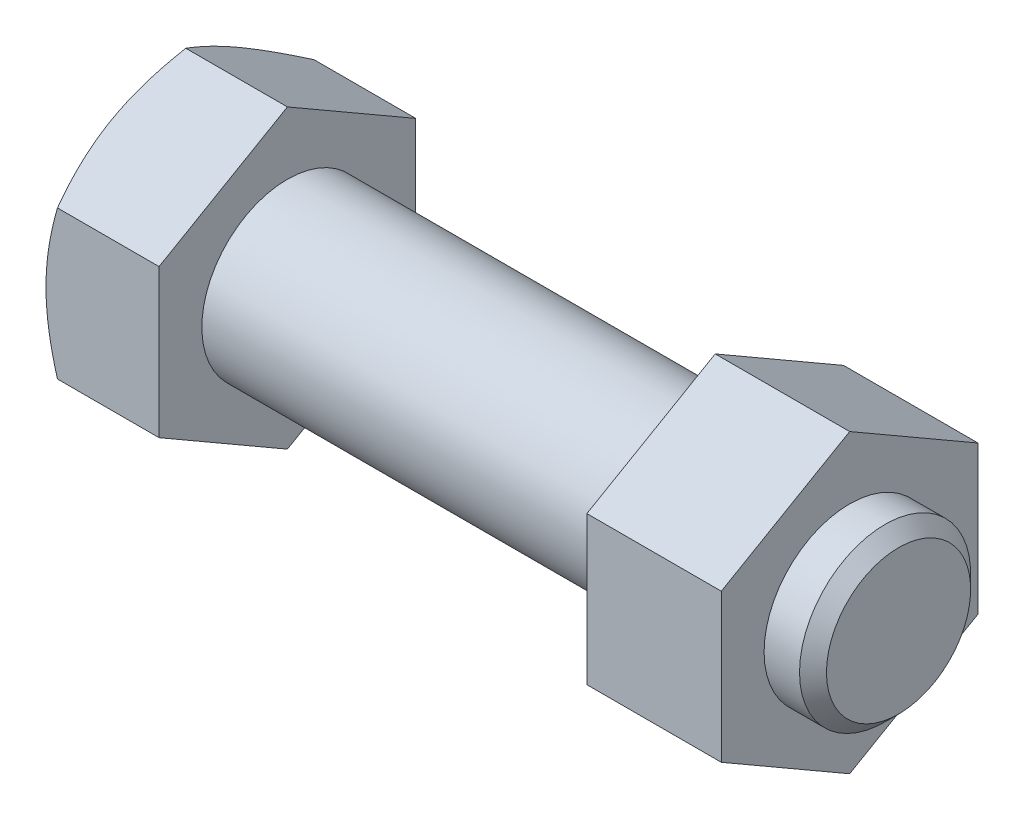
SolidWorks part; units mm, degrees
extrude "BaseHead" add sketch "Sketch1" along normal blind 9.25
sketch "Sketch1" plane through (0, 0, 0) normal (1, 0, 0) x (0, 0, -1)
  line L0 (10.5, 6.0622) -> (10.5, -6.0622)
  line L1 (-10.5, 6.0622) -> (-10.5, -6.0622)
  line L2 (10.5, -6.0622) -> (0, -12.1244)
  line L3 (0, -12.1244) -> (-10.5, -6.0622)
  line L4 (10.5, 6.0622) -> (0, 12.1244)
  line L5 (0, 12.1244) -> (-10.5, 6.0622)
  dimension "Width_flats" = 21
  dimension "D2" = 120
  dimension "D3" = 10.5
  dimension "D4" = 10.5
  dimension "D5" = 10.5
material "Dacromet"
ref_plane "Plane1" through (0, 0, 0) normal (0, 0, 1) x (1, 0, 0)
ref_plane "Plane2" through (0, 0, 0) normal (0, 1, 0) x (1, 0, 0)
ref_plane "Plane3" through (0, 0, 0) normal (1, 0, 0) x (0, 0, -1)
sketch "BodySke" plane through (0, 0, 0) normal (0, 0, 1) x (1, 0, 0)
  line L0 (0, 6.0622) -> (0, -6.0622) construction
  line L1 (0, 0) -> (59.25, 0)
  line L2 (0, 0) -> (0, 7)
  line L3 (0, 7) -> (58.1485, 7)
  line L4 (59.25, 0) -> (59.25, 5.8985)
  line L5 (9.25, 12.1244) -> (9.25, 6.0622) construction
  line L6 (59.25, 5.8985) -> (58.1485, 7)
  line L7 (0, 0) -> (96.52, 0) construction
  line L8 (59.25, -5.8985) -> (58.1485, -7) construction
  line L9 (0, -7) -> (58.1485, -7) construction
  line L10 (11.25, 15.24) -> (11.25, -1.27) construction
  line L11 (25.25, 15.24) -> (25.25, -1.27) construction
  line L12 (9.25, 6.0622) -> (9.25, -6.0622) construction
  dimension "Diameter" = 14
  dimension "Advance" = 2
revolve "BaseBody" add sketch "BodySke"
cosmetic thread "ThreadCosmetic" [suppressed]
fillet "HeadFillet" [suppressed] radius 0.6
sketch "Sketch3" plane through (0, 0, 0) normal (0, 0, 1) x (1, 0, 0)
  line L0 (0, 10.5) -> (3.8246, 17.1244)
  line L1 (0, 12.1244) -> (0, 6.0622) construction
  line L2 (3.8246, 17.1244) -> (3.8246, 22.1244)
  line L3 (3.8246, 22.1244) -> (-10, 22.1244)
  line L4 (-10, 22.1244) -> (-10, 10.5)
  line L5 (-10, 10.5) -> (0, 10.5)
  line L6 (0, 0) -> (99.06, 0) construction
  line L7 (9.25, 12.1244) -> (0, 12.1244) construction
  dimension "D1" = 10.5
  dimension "D2" = 5
  dimension "D3" = 10
  dimension "D4" = 5
  dimension "Head_ch_ang" = 30
revolve "HeadChamfer" cut sketch "Sketch3" angle 360 about L6
sketch "ThdSchSke" plane through (0, 0, 0) normal (0, 0, 1) x (1, 0, 0)
  line L0 (25.25, -5.8985) -> (24.4787, -7)
  line L1 (25.25, -5.8985) -> (26.0213, -7)
  line L2 (26.0213, -7) -> (26.0213, -8.75)
  line L3 (-3.175, 0) -> (5.1513, 0) construction
  line L5 (26.0213, -8.75) -> (24.4787, -8.75)
  line L6 (24.4787, -8.75) -> (24.4787, -7)
  dimension "Thread_minor" = 11.797
  dimension "Diameter" = 14
  dimension "Start" = 25.25
revolve "ThreadSchematic" [suppressed] cut sketch "ThdSchSke" angle 360 about L3
pattern_linear "ThdSchPat" [suppressed]
ref_plane "Plane4" through (44.25, 0, 0) normal (1, 0, 0) x (0, 0, -1)
sketch "Sketch4" plane through (44.25, 0, 0) normal (1, 0, 0) x (0, 0, -1)
  line L1 (0, 12.1244) -> (-10.5, 6.0622)
  line L2 (-10.5, 6.0622) -> (-10.5, -6.0622)
  line L3 (-10.5, -6.0622) -> (0, -12.1244)
  line L4 (0, -12.1244) -> (10.5, -6.0622)
  line L5 (10.5, -6.0622) -> (10.5, 6.0622)
  line L6 (10.5, 6.0622) -> (0, 12.1244)
  circle A0 centre (0, 0) radius 10.5 construction
extrude "Boss-Extrude1" add sketch "Sketch4" along normal blind 11
equation "\"D3@Sketch1\" = \"Width_flats@Sketch1\" / 2"
equation "\"D4@Sketch1\" = \"D3@Sketch1\""
equation "\"D5@Sketch1\" = \"D4@Sketch1\""
equation "\"Thread_minor@ThreadCosmetic\" = \"Minor_dia@BodySke\""
equation "\"D1@Sketch3\" = \"Width_flats@Sketch1\" / 2"
equation "' \"D1@Sketch4\" = \"Width_flats@Sketch1\""
equation "\"Thread_length@ThreadCosmetic\" = ((sgn( (\"Length@BodySke\" - \"Advance@BodySke\" ) - \"Thread_nom@BodySke\" )-1)*( (\"Length@BodySke\" - \"Advance@BodySke\" ) - \"Thread_nom@BodySke\" ))/-2+ \"Thread_nom@BodySke\""
equation "\"Thread_minor@ThdSchSke\" = \"Minor_dia@BodySke\""
equation "\"Diameter@ThdSchSke\" = \"Diameter@BodySke\""
equation "\"Overcut@ThdSchSke\" = \"Diameter@BodySke\" * 1.25"
equation "\"Start@ThdSchSke\" = \"Head_ht@BaseHead\" + \"Length@BodySke\" - \"Thread_length@ThreadCosmetic\"  '---Non-countersunk---"
equation "\"Num_threads@ThdSchPat\" = int( \"Thread_length@ThreadCosmetic\" / \"Advance@BodySke\" + 0.999 )  + 1"
equation "\"Advance@ThdSchPat\" = \"Thread_length@ThreadCosmetic\" /  (\"Num_threads@ThdSchPat\" - 1) 'relax it"
equation "\"Num_threads@ThdSchPat\" = \"Num_threads@ThdSchPat\" - sgn( \"Num_threads@ThdSchPat\" - 1) '---chamfered tips only---"
